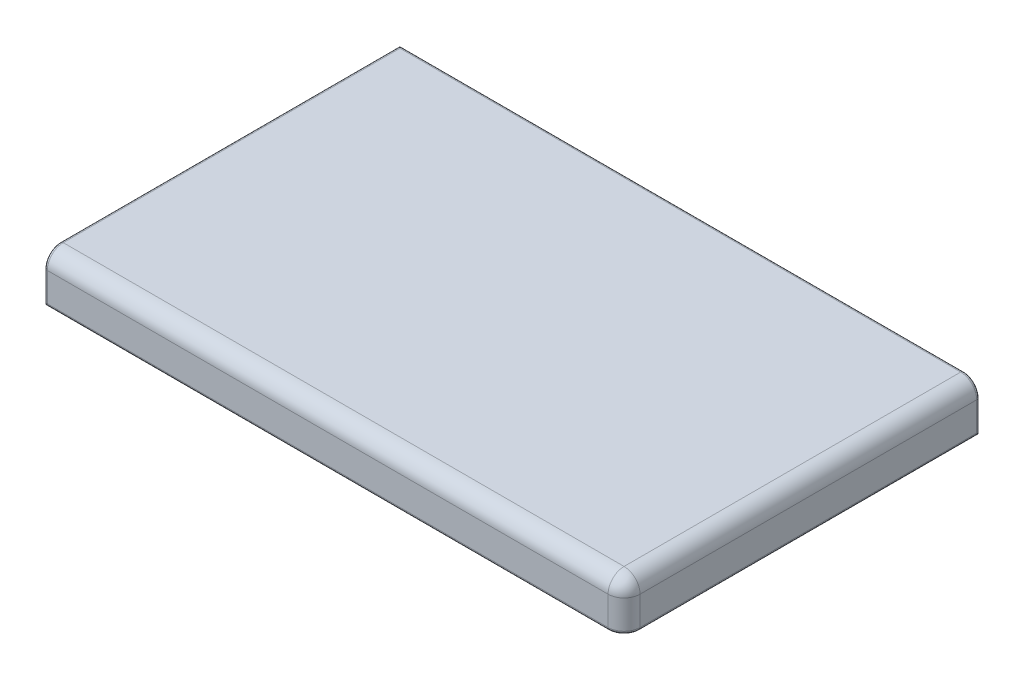
SolidWorks part; units mm, degrees
ref_plane "Front Plane" through (0, 0, 0) normal (0, 0, 1) x (1, 0, 0)
ref_plane "Top Plane" through (0, 0, 0) normal (0, 1, 0) x (1, 0, 0)
ref_plane "Right Plane" through (0, 0, 0) normal (1, 0, 0) x (0, 0, -1)
sketch "Sketch2" plane through (0, 0, 0) normal (0, 1, 0) x (1, 0, 0)
  line L1 (0, -85.7246) -> (1811.0059, -85.7246)
  line L2 (0, -85.7246) -> (0, -1196.8566)
  line L3 (0, -1196.8566) -> (1811.0059, -1196.8566)
  line L4 (1811.0059, -85.7246) -> (1811.0059, -1196.8566)
extrude "Boss-Extrude1" add sketch "Sketch2" along normal blind 150
fillet "Fillet1" radius 50 1 edges at (1811.0059, 150, 641.2906)
fillet "Fillet2" radius 50 3 edges at (1811.0059, 50, 1196.8566) (1796.3612, 135.3553, 1196.8566) (880.503, 150, 1196.8566)
fillet "Fillet3" radius 10 9 edges at (1796.3612, 0, 1182.2119) (1796.3612, 135.3553, 85.7246) (0, 135.3553, 1182.2119) (1811.0059, 50, 85.7246) (1811.0059, 0, 616.2906) (0, 50, 1196.8566) (880.503, 0, 1196.8566) (880.503, 150, 85.7246) (0, 150, 616.2906)
